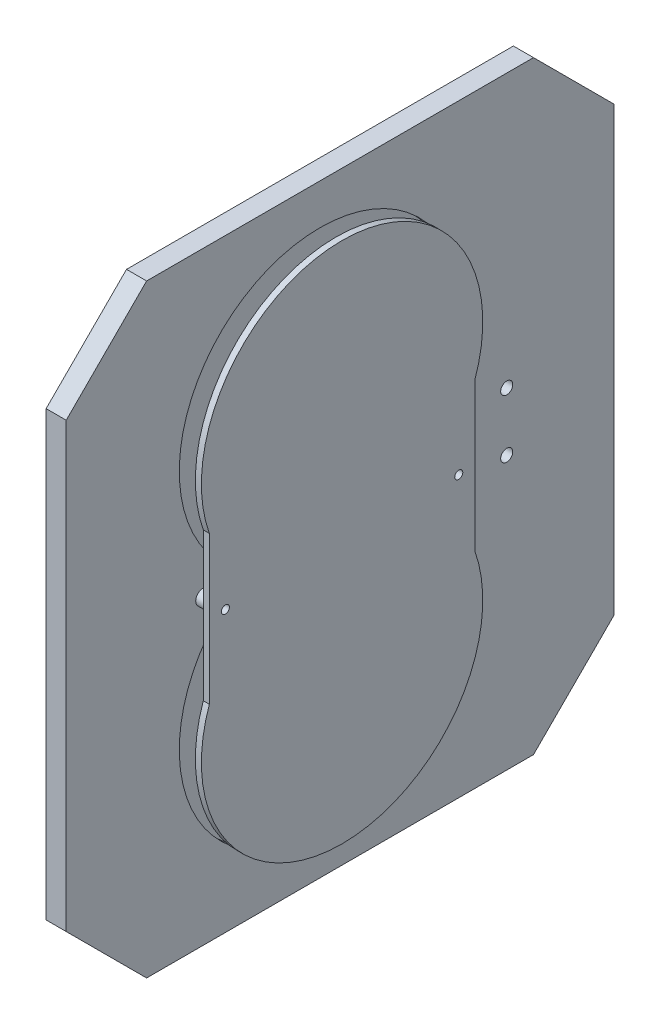
SolidWorks part; units mm, degrees
ref_plane "Front Plane" through (0, 0, 0) normal (0, 0, 1) x (1, 0, 0)
ref_plane "Top Plane" through (0, 0, 0) normal (0, 1, 0) x (1, 0, 0)
ref_plane "Right Plane" through (0, 0, 0) normal (1, 0, 0) x (0, 0, -1)
sketch "Sketch1" plane through (0, 0, 0) normal (1, 0, 0) x (0, 0, -1)
  line L0 (-75.0007, -75.0866) -> (41.0434, -75.0866)
  line L3 (-75.0007, 75.0866) -> (41.0434, 75.0866)
  line L4 (-75.0007, -75.0866) -> (-55.7305, -55.7944) construction
  line L5 (41.0434, 75.0866) -> (41.0434, -75.0866)
  line L6 (-55.7305, 55.7944) -> (-75.0007, 75.0866) construction
  line L7 (-75.0007, 75.0866) -> (-95.199, 75.0866)
  line L8 (-95.199, 75.0866) -> (-95.199, -75.0866)
  line L9 (-95.199, -75.0866) -> (-75.0007, -75.0866)
  line L11 (-6.3063, -6.3135) -> (0, 0) construction
  line L12 (-55.097, 0) -> (-55.097, 2.7451)
  line L13 (-55.097, 0) -> (-55.097, -2.7451)
  line L18 (-9.0458, 0) -> (-9.0458, 2.7491)
  line L19 (-9.0458, 0) -> (-9.0458, -2.7491)
  circle A0 centre (14.3842, 7.2476) radius 1.5
  circle A1 centre (14.3842, -7.2476) radius 1.5
  arc A8 (-8.3987, 4.2221) -> (-55.7443, 4.2183) centre (-32.0736, 30) ccw
  arc A9 (-55.7443, -4.2183) -> (-8.3987, -4.2221) centre (-32.0736, -30) ccw
  arc A10 (-55.097, -2.7451) -> (-55.7443, -4.2183) centre (-57.097, -2.7451) cw
  arc A11 (-55.097, 2.7451) -> (-55.7443, 4.2183) centre (-57.097, 2.7451) ccw
  arc A12 (-9.0458, -2.7491) -> (-8.3987, -4.2221) centre (-7.0458, -2.7491) ccw
  arc A13 (-9.0458, 2.7491) -> (-8.3987, 4.2221) centre (-7.0458, 2.7491) cw
  point P1 (0, 0)
  point P24 (14.3842, -30)
  point P25 (14.3842, 30)
  dimension "D1" = 2
  dimension "D2" = 2
extrude "Boss-Extrude1" add sketch "Sketch1" against normal blind 1 and the other way blind 4
sketch "Sketch4" plane through (4, 0, 0) normal (1, 0, 0) x (0, 0, -1)
  circle A0 centre (14.3842, 7.2476) radius 1.5
  circle A1 centre (14.3842, -7.2476) radius 1.5
sketch "Sketch8" plane through (4, 0, 0) normal (1, 0, 0) x (0, 0, -1)
  line L1 (-75.0007, 75.0866) -> (41.0434, 75.0866) construction
  line L7 (-75.0007, -75.0866) -> (41.0434, -75.0866) construction
  line L16 (41.0434, 75.0866) -> (41.0434, 55.0866)
  line L17 (41.0434, 75.0866) -> (41.0434, -75.0866) construction
  line L18 (41.0434, 55.0866) -> (21.0434, 75.0866)
  line L19 (21.0434, 75.0866) -> (41.0434, 75.0866)
  line L20 (41.0434, -75.0866) -> (41.0434, -55.0866)
  line L21 (41.0434, -55.0866) -> (21.0434, -75.0866)
  line L22 (21.0434, -75.0866) -> (41.0434, -75.0866)
  line L24 (-95.199, 75.0866) -> (-95.199, -75.0866) construction
  line L25 (-95.199, 55.0866) -> (-95.199, 75.0866)
  line L28 (-95.199, -55.0866) -> (-95.199, -75.0866)
  line L30 (-95.199, 75.0866) -> (-75.199, 75.0866)
  line L31 (-75.0007, 75.0866) -> (-95.199, 75.0866) construction
  line L32 (-95.199, 55.0866) -> (-75.199, 75.0866)
  line L33 (-95.199, -75.0866) -> (-75.199, -75.0866)
  line L34 (-95.199, -75.0866) -> (-75.0007, -75.0866) construction
  line L35 (-95.199, -55.0866) -> (-75.199, -75.0866)
extrude "Cut-Extrude2" cut sketch "Sketch8" against normal through all
sketch "Sketch9" plane through (4, 0, 0) normal (1, 0, 0) x (0, 0, -1)
  line L0 (-55.097, 0) -> (-55.097, 2.7451)
  line L1 (-55.097, 0) -> (-55.097, -2.7451)
  line L2 (-9.0458, 0) -> (-9.0458, 2.7491)
  line L3 (-9.0458, 0) -> (-9.0458, -2.7491)
  arc A0 (-8.3987, 4.2221) -> (-55.7443, 4.2183) centre (-32.0736, 30) ccw
  arc A1 (-55.7443, -4.2183) -> (-8.3987, -4.2221) centre (-32.0736, -30) ccw
  arc A2 (-9.0458, 2.7491) -> (-8.3987, 4.2221) centre (-7.0458, 2.7491) cw
  arc A3 (-9.0458, -2.7491) -> (-8.3987, -4.2221) centre (-7.0458, -2.7491) ccw
  arc A4 (-55.097, -2.7451) -> (-55.7443, -4.2183) centre (-57.097, -2.7451) cw
  arc A5 (-55.097, 2.7451) -> (-55.7443, 4.2183) centre (-57.097, 2.7451) ccw
  dimension "D1" = 2
extrude "Boss-Extrude2" add sketch "Sketch9" against normal blind 3 from offset 2 offset against normal yes
sketch "Sketch10" plane through (2, 0, 0) normal (1, 0, 0) x (0, 0, -1)
  circle A0 centre (-32.0736, 30) radius 9
  circle A1 centre (-32.0736, -30) radius 3
extrude "Cut-Extrude3" cut sketch "Sketch10" against normal blind 3
sketch "Sketch11" plane through (4, 0, 0) normal (1, 0, 0) x (0, 0, -1)
  circle A0 centre (-61.097, 0) radius 1.8866
  circle A1 centre (-3.0458, 0) radius 2
  circle A2 centre (-61.097, 0) radius 1
  circle A3 centre (-3.0458, 0) radius 1
extrude "Boss-Extrude3" add sketch "Sketch11" along normal blind 4
sketch "Sketch12" plane through (8, 0, 0) normal (1, 0, 0) x (0, 0, -1)
  line L1 (-65.097, 0) -> (-65.097, 18.4044)
  line L2 (-65.097, 0) -> (-65.097, -18.4044)
  line L4 (0.9542, 0) -> (0.9542, 18.4169)
  line L5 (0.9542, 0) -> (0.9542, -18.4169)
  arc A0 (-8.3987, 4.2221) -> (-55.7443, 4.2183) centre (-32.0736, 30) ccw construction
  arc A1 (-55.7443, -4.2183) -> (-8.3987, -4.2221) centre (-32.0736, -30) ccw construction
  arc A2 (0.9542, 18.4169) -> (-65.097, 18.4044) centre (-32.0736, 30) ccw
  arc A3 (-65.097, -18.4044) -> (0.9542, -18.4169) centre (-32.0736, -30) ccw
  circle A4 centre (-61.097, 0) radius 1
  circle A5 centre (-3.0458, 0) radius 1
extrude "Boss-Extrude4" add sketch "Sketch12" along normal blind 1.5
